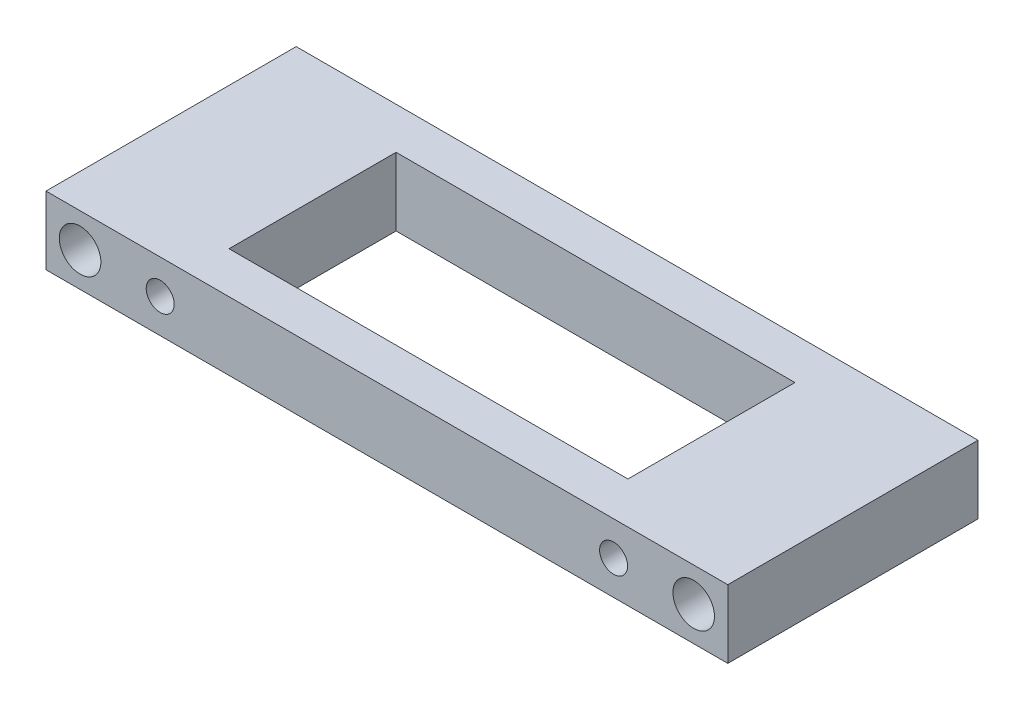
SolidWorks part; units mm, degrees
ref_plane "Front Plane" through (0, 0, 0) normal (0, 0, 1) x (1, 0, 0)
ref_plane "Top Plane" through (0, 0, 0) normal (0, 1, 0) x (1, 0, 0)
ref_plane "Right Plane" through (0, 0, 0) normal (1, 0, 0) x (0, 0, -1)
sketch "Sketch1" plane through (0, 0, 0) normal (0, 0, 1) x (1, 0, 0)
  line L0 (-58.5, 20) -> (-58.5, 0) construction
  line L1 (0, 0) -> (-100, 0)
  line L2 (0, 0) -> (0, 20)
  line L3 (0, 20) -> (-100, 20)
  line L4 (-100, 0) -> (-100, 20)
  circle A0 centre (-90, 10) radius 6.1
  circle A1 centre (-66.5, 10) radius 4.1
  point P9 (-100, 10)
  dimension "D3" = 12.2
  dimension "D4" = 8.2
  dimension "D1" = 100
  dimension "D2" = 20
  dimension "D5" = 23.5
  dimension "D6" = 10
  dimension "D7" = 8
  dimension "D8" = 41.5
extrude "Boss-Extrude1" add sketch "Sketch1" along normal blind 40
sketch "Sketch2" plane through (0, 0, 0) normal (0, 0, -1) x (-1, 0, 0)
  line L1 (100, 20) -> (0, 20)
  line L2 (100, 20) -> (100, 0)
  line L3 (100, 0) -> (0, 0)
  line L4 (0, 20) -> (0, 0)
extrude "Boss-Extrude2" add sketch "Sketch2" along normal blind 33.4
sketch "Sketch3" plane through (0, 20, 0) normal (0, 1, 0) x (1, 0, 0)
  line L0 (0, -40) -> (0, 33.4) construction
  line L1 (0, 21.2) -> (-58.5, 21.2)
  line L2 (0, 21.2) -> (0, -27.8)
  line L3 (0, -27.8) -> (-58.5, -27.8)
  line L4 (-58.5, 21.2) -> (-58.5, -27.8)
  line L5 (-100, -40) -> (-100, 33.4) construction
  line L6 (-100, 33.4) -> (0, 33.4) construction
  line L7 (0, -40) -> (-100, -40) construction
  dimension "D1" = 41.5
  dimension "D2" = 12.2
  dimension "D3" = 12.2
extrude "Cut-Extrude1" cut sketch "Sketch3" against normal up to next
mirror "Mirror2" about plane through (0, 0, 40) normal (-1, 0, 0) of "Boss-Extrude2", "Cut-Extrude1", "Boss-Extrude1"
